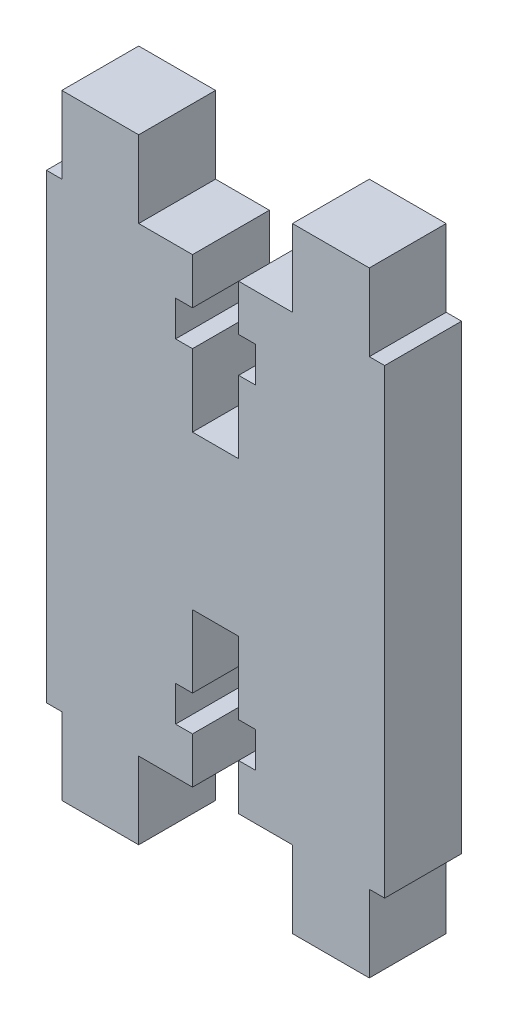
SolidWorks part; units mm, degrees
ref_plane "Front Plane" through (0, 0, 0) normal (0, 0, 1) x (1, 0, 0)
ref_plane "Top Plane" through (0, 0, 0) normal (0, 1, 0) x (1, 0, 0)
ref_plane "Right Plane" through (0, 0, 0) normal (1, 0, 0) x (0, 0, -1)
sketch "Sketch1" plane through (0, 0, 0) normal (0, 0, 1) x (1, 0, 0)
  line L0 (0, 30) -> (1, 30)
  line L1 (0, 0) -> (22, 0) construction
  line L2 (0, 0) -> (0, 30)
  line L3 (0, 30) -> (22, 30) construction
  line L4 (22, 0) -> (22, 30)
  line L5 (21, 30) -> (22, 30)
  line L6 (22, 0) -> (21, 0)
  line L7 (1, 0) -> (0, 0)
  line L8 (11, 30) -> (11, 38.7792) construction
  line L9 (12.5, 30) -> (16, 30)
  line L10 (16, 35) -> (21, 35)
  line L11 (21, 35) -> (21, 30)
  line L12 (16, 35) -> (16, 30)
  line L13 (9.5, 30) -> (6, 30)
  line L14 (6, 30) -> (6, 35)
  line L15 (6, 35) -> (1, 35)
  line L16 (1, 35) -> (1, 30)
  line L17 (12.5, 30) -> (9.5, 30) construction
  line L18 (9.5, 30) -> (9.5, 27)
  line L19 (9.5, 24.7) -> (8.4, 24.7)
  line L20 (13.6, 27) -> (13.6, 24.7)
  line L21 (8.4, 27) -> (9.5, 27)
  line L22 (9.5, 24.7) -> (9.5, 20)
  line L23 (9.5, 20) -> (12.5, 20)
  line L24 (12.5, 20) -> (12.5, 24.7)
  line L25 (12.5, 27) -> (13.6, 27)
  line L26 (8.4, 24.7) -> (8.4, 27)
  line L27 (13.6, 24.7) -> (12.5, 24.7)
  line L28 (12.5, 27) -> (12.5, 30)
  line L29 (11, 20) -> (11, 30) construction
  line L30 (11, 0) -> (11, 11.2208) construction
  line L31 (9.5, 0) -> (6, 0)
  line L32 (6, -5) -> (1, -5)
  line L33 (1, -5) -> (1, 0)
  line L34 (6, -5) -> (6, 0)
  line L35 (12.5, 0) -> (16, 0)
  line L36 (16, 0) -> (16, -5)
  line L37 (16, -5) -> (21, -5)
  line L38 (21, -5) -> (21, 0)
  line L39 (9.5, 0) -> (12.5, 0) construction
  line L40 (12.5, 0) -> (12.5, 3)
  line L41 (12.5, 5.3) -> (13.6, 5.3)
  line L42 (8.4, 3) -> (8.4, 5.3)
  line L43 (13.6, 3) -> (12.5, 3)
  line L44 (12.5, 5.3) -> (12.5, 10)
  line L45 (12.5, 10) -> (9.5, 10)
  line L46 (9.5, 10) -> (9.5, 5.3)
  line L47 (9.5, 3) -> (8.4, 3)
  line L48 (13.6, 5.3) -> (13.6, 3)
  line L49 (8.4, 5.3) -> (9.5, 5.3)
  line L50 (9.5, 3) -> (9.5, 0)
  line L51 (11, 10) -> (11, 0) construction
  point P11 (11, 0)
  dimension "D1" = 30
  dimension "D2" = 22
  dimension "D3" = 10
  dimension "D4" = 5
  dimension "D5" = 5
  dimension "D6" = 5.2
  dimension "D7" = 3
  dimension "D8" = 2.3
  dimension "D9" = 3
  dimension "D10" = 10
  dimension "D11" = 10
  dimension "D12" = 5
  dimension "D13" = 5
  dimension "D14" = 5.2
  dimension "D15" = 3
  dimension "D16" = 2.3
  dimension "D17" = 3
  dimension "D18" = 10
extrude "Boss-Extrude1" add sketch "Sketch1" along normal blind 5
